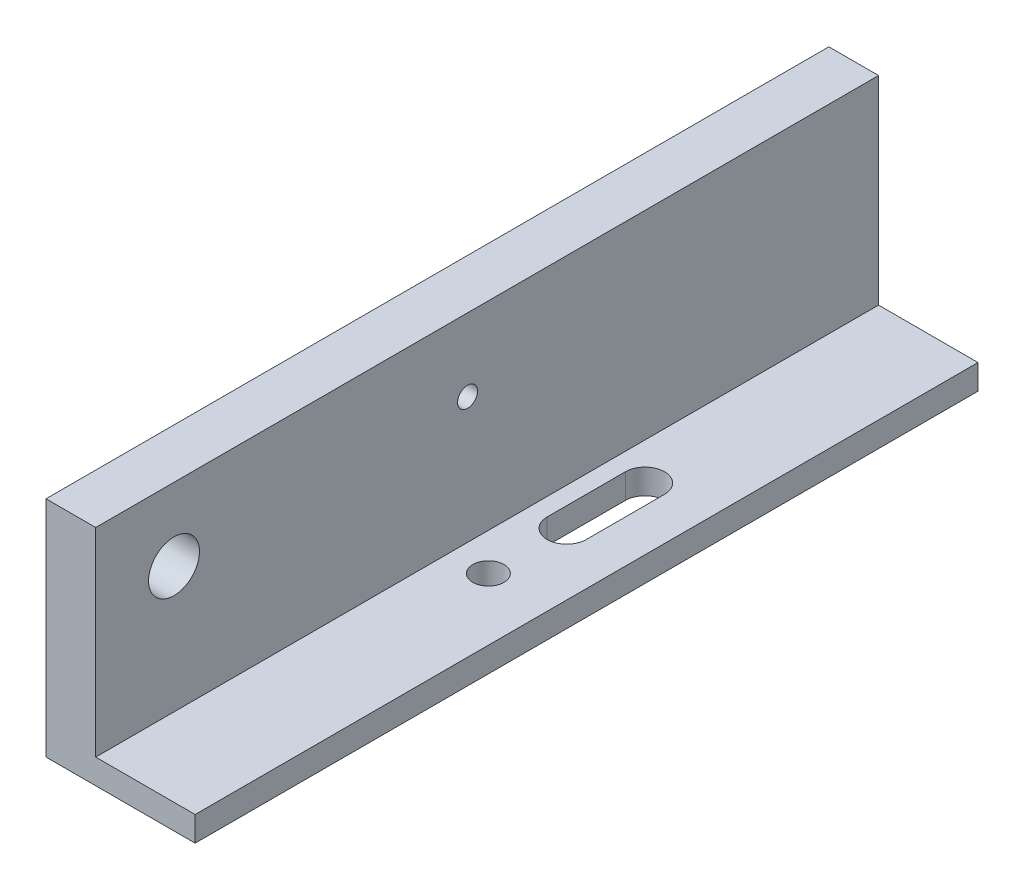
SolidWorks part; units mm, degrees
ref_plane "Alzado" through (0, 0, 0) normal (0, 0, 1) x (1, 0, 0)
ref_plane "Planta" through (0, 0, 0) normal (0, 1, 0) x (1, 0, 0)
ref_plane "Vista lateral" through (0, 0, 0) normal (1, 0, 0) x (0, 0, -1)
sketch "Croquis1" plane through (0, 0, 0) normal (0, 0, 1) x (1, 0, 0)
  line L0 (0, 28.575) -> (0, -28.575)
  line L1 (0, 0) -> (-1647.5859, 0) construction
  line L2 (0, 28.575) -> (38.1, 28.575)
  line L3 (0, -28.575) -> (38.1, -28.575)
  line L4 (38.1, 28.575) -> (38.1, 22.225)
  line L5 (38.1, -28.575) -> (38.1, -22.225)
  line L6 (38.1, 22.225) -> (12.7, 22.225)
  line L7 (38.1, -22.225) -> (12.7, -22.225)
  line L8 (12.7, 22.225) -> (12.7, -22.225)
  line L9 (12.7, 22.225) -> (12.7, 28.575)
  dimension "D1" = 6.35
  dimension "D2" = 57.15
  dimension "D3" = 12.7
  dimension "D4" = 25.4
extrude "Saliente-Extruir1" add sketch "Croquis1" along normal mid plane 200 contours L1 L8 L9 L2 L0 | L8 L1 L0 L3 L5 L7
sketch "Croquis2" plane through (0, 0, 0) normal (0, 1, 0) x (1, 0, 0)
  line L0 (0, 50) -> (0, -50)
  line L1 (0, -50) -> (-19.05, -30.95)
  line L2 (-19.05, -30.95) -> (-19.05, 30.95)
  line L3 (-19.05, 30.95) -> (0, 50)
  line L6 (200000, 0) -> (-201647.5859, 0) construction
  point P5 (-19.05, 0)
  dimension "D2" = 45
  dimension "D3" = 19.05
  dimension "D4" = 100
extrude "Saliente-Extruir2" add sketch "Croquis2" along normal mid plane 12.7
hole_wizard "Taladro roscado 1/4-201" [suppressed] positions "Croquis3" profile "Croquis4" tap size "1/4-20" standard "Ansi Inch"
sketch "Croquis3" plane through (0, -28.575, 0) normal (0, -1, 0) x (-1, 0, 0)
  line L0 (0, 0) -> (-50000, 0) construction
  line L1 (0, -50) -> (0, 50) construction
  point P0 (-25.4, -50)
  point P7 (0, 0)
  point P10 (-25.4, 50)
  dimension "D1" = 50
sketch "Croquis4" plane through (25.4, -28.575, 50) normal (1, 0, 0) x (0, 0, -1)
  line L0 (0, 0) -> (0, 6.35)
  line L1 (0, 6.35) -> (2.5527, 6.35)
  line L2 (2.5527, 6.35) -> (2.5527, 0)
  line L5 (2.5527, 0) -> (0, 0)
  line L11 (0, -6.35) -> (0, 107.95) construction
  dimension "Diámetro de perforador para roscar hasta el siguiente" = 5.1054
  dimension "Profundidad de perforador para roscar hasta el siguiente" = 6.35
cosmetic thread "Rosca de taladro7" [suppressed] parameters "D1"=6.35, "D2"=6.35
cosmetic thread "Rosca de taladro8" [suppressed] parameters "D1"=6.35, "D2"=6.35
ref_plane "Plano1" through (0, 0, 50) normal (0, 0, 1) x (1, 0, 0)
hole_wizard "Taladro roscado 1/4-202" positions "Croquis5" profile "Croquis6" tap size "1/4-20" standard "Ansi Inch" end condition through all
sketch "Croquis5" plane through (0, 0, 50) normal (0, 0, 1) x (1, 0, 0)
  line L0 (0, -6.35) -> (-19.05, -6.35) construction
  point P0 (-9.525, 0)
  point P6 (-9.525, -6.35)
sketch "Croquis6" plane through (-9.525, 0, 50) normal (1, 0, 0) x (0, -1, 0)
  line L0 (0, 0) -> (0, 150)
  line L1 (0, 150) -> (2.5527, 150)
  line L2 (2.5527, 150) -> (2.5527, 0)
  line L5 (2.5527, 0) -> (0, 0)
  line L11 (0, -6.35) -> (0, 107.95) construction
  dimension "Diámetro de perforador para roscar hasta el siguiente" = 5.1054
  dimension "Profundidad de perforador para roscar hasta el siguiente" = 150
cosmetic thread "Rosca de taladro6" parameters "D2"=6.35
hole_wizard "Taladro roscado #8-321" positions "Croquis7" profile "Croquis9" tap size "#8-32" standard "Ansi Inch"
sketch "Croquis7" plane through (-19.05, 0, 0) normal (-1, 0, 0) x (0, 0, 1)
  point P0 (0, 0)
sketch "Croquis9" plane through (-19.05, 0, 0) normal (0, 1, 0) x (0, 0, 1)
  line L0 (0, 0) -> (0, 5.8003)
  line L1 (0, 5.8003) -> (1.7272, 4.7625)
  line L2 (1.7272, 4.7625) -> (1.7272, 0)
  line L5 (1.7272, 0) -> (0, 0)
  line L10 (0, 5.8003) -> (-1.7272, 4.7625) construction
  line L11 (0, -6.35) -> (0, 107.95) construction
  dimension "Diámetro de perforador para roscar" = 3.4544
  dimension "Profundidad de perforador para roscar" = 4.7625
  dimension "Ángulo de perforador" = 118
sketch "Croquis10" plane through (0, 0, 0) normal (-1, 0, 0) x (0, 0, 1)
  circle A0 centre (80, 10) radius 6.5
  dimension "D1" = 13
  dimension "D2" = 10
  dimension "D3" = 80
extrude "Cortar-Extruir1" cut sketch "Croquis10" against normal through all
sketch "Croquis13" plane through (0, -28.575, 0) normal (0, -1, 0) x (1, 0, 0)
  line L0 (22.225, -10.795) -> (22.225, -30.7901) construction
  line L1 (27.225, -10.795) -> (27.225, -30.7901)
  line L2 (17.225, -10.795) -> (17.225, -30.7901)
  line L4 (22.225, -5.6727) -> (22.225, -35.5586) construction
  arc A0 (27.225, -10.795) -> (17.225, -10.795) centre (22.225, -10.795) ccw
  arc A1 (17.225, -30.7901) -> (27.225, -30.7901) centre (22.225, -30.7901) ccw
  point P2 (22.225, -20.7926)
  dimension "D1" = 10
extrude "Cortar-Extruir2" cut sketch "Croquis13" against normal up to surface (6.35 mm away) up to face at (25.4, -22.225, 0)
hole_wizard "Taladro roscado 1/4-203" positions "Croquis14" profile "Croquis15" tap size "1/4-20" standard "Ansi Inch"
sketch "Croquis14" plane through (12.7, 0, 0) normal (-1, 0, 0) x (0, 0, 1)
  arc A0 (6.1394, 23.0236) -> (5, 10) centre (80, 10) ccw construction
  point P0 (5, 10)
cosmetic thread "Rosca de taladro9" parameters "D1"=13, "D2"=6.35
sketch "Croquis15" plane through (12.7, 10, 5) normal (0, 1, 0) x (0, 0, -1)
  line L0 (0, 0) -> (0, 14.5338)
  line L1 (0, 14.5338) -> (2.5527, 13)
  line L2 (2.5527, 13) -> (2.5527, 0)
  line L5 (2.5527, 0) -> (0, 0)
  line L10 (0, 14.5338) -> (-2.5527, 13) construction
  line L11 (0, -6.35) -> (0, 107.95) construction
  dimension "Diámetro de perforador para roscar" = 5.1054
  dimension "Profundidad de perforador para roscar" = 13
  dimension "Ángulo de perforador" = 118
hole_wizard "3/8-16 Tapped Hole1" positions "Sketch1" profile "Sketch2" tap size "3/8-16" standard "ANSI Inch"
sketch "Sketch1" plane through (0, -28.575, 0) normal (0, -1, 0) x (-1, 0, 0)
  line L0 (-22.225, 10.795) -> (-22.225, 30.7901) construction
  point P0 (-22.225, -9.205)
  point P2 (0, 0)
  dimension "D1" = 20
sketch "Sketch2" plane through (22.225, -28.575, 9.205) normal (1, 0, 0) x (0, 0, -1)
  line L0 (0, 0) -> (0, 26.1947)
  line L1 (0, 26.1947) -> (3.9687, 23.81)
  line L2 (3.9687, 23.81) -> (3.9687, 0)
  line L5 (3.9687, 0) -> (0, 0)
  line L10 (0, 26.1947) -> (-3.9687, 23.81) construction
  line L11 (0, -6.35) -> (0, 107.95) construction
  dimension "Tap Drill Dia." = 7.9375
  dimension "Tap Drill Depth" = 23.81
  dimension "Drill Angle" = 118
cosmetic thread "Hole Thread1" parameters "D1"=6.35, "D2"=9.525
